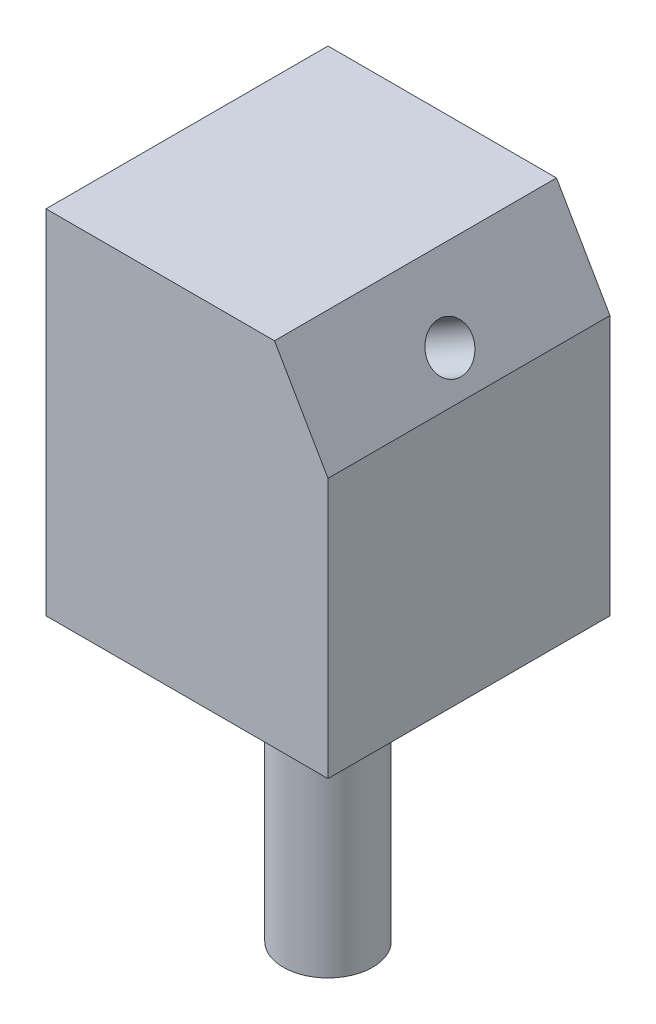
SolidWorks part; units mm, degrees
ref_plane "Alzado" through (0, 0, 0) normal (0, 0, 1) x (1, 0, 0)
ref_plane "Planta" through (0, 0, 0) normal (0, 1, 0) x (1, 0, 0)
ref_plane "Vista lateral" through (0, 0, 0) normal (1, 0, 0) x (0, 0, -1)
sketch "Croquis1" plane through (0, 0, 0) normal (0, 1, 0) x (1, 0, 0)
  line L1 (-6.1404, -5.7018) -> (13.8596, -5.7018)
  line L2 (-6.1404, -5.7018) -> (-6.1404, 14.2982)
  line L3 (-6.1404, 14.2982) -> (13.8596, 14.2982)
  line L4 (13.8596, -5.7018) -> (13.8596, 14.2982)
  dimension "D1" = 20
  dimension "D2" = 20
extrude "Saliente-Extruir1" add sketch "Croquis1" along normal blind 30
sketch "Croquis2" plane through (0, 0, 0) normal (0, 0, 1) x (1, 0, 0)
  line L0 (13.8596, 24.6924) -> (13.8596, 18.4443)
  line L1 (13.8596, 30) -> (13.8596, 0) construction
  line L2 (13.8596, 18.4443) -> (11.1508, 23.1246) construction
  line L3 (11.1508, 23.1246) -> (13.8596, 24.6924) construction
  line L5 (13.8596, 18.4443) -> (11.1508, 23.1246)
  line L6 (11.1508, 23.1246) -> (13.8596, 24.6924)
extrude "Cortar-Extruir1" cut sketch "Croquis2" against normal through all both and the other way through all
sketch "Croquis4" plane through (18.3783, 10.6373, 0) normal (0.8655, 0.5009, 0) x (0, 0, -1)
  circle A0 centre (4.2982, 11.7243) radius 1.5875
  dimension "D1" = 3.175
extrude "Cortar-Extruir2" cut sketch "Croquis4" against normal blind 30
sketch "Croquis7" plane through (0, 0, 0) normal (0, -1, 0) x (1, 0, 0)
  circle A0 centre (3.8596, -4.2982) radius 3.175
  dimension "D1" = 6.35
extrude "Saliente-Extruir2" add sketch "Croquis7" along normal blind 20
sketch "Croquis8" plane through (0, 0, 5.7018) normal (0, 0, 1) x (1, 0, 0)
  line L0 (12.5052, 20.7845) -> (-24.4883, -0.6272) construction
  line L1 (11.1508, 23.1246) -> (13.8596, 18.4443) construction
  line L2 (-6.1404, 0) -> (13.8596, 0) construction
  point P6 (3.8596, 0)
  dimension "D1" = 28.3479
sketch "Croquis9" plane through (0, 0, 5.7018) normal (0, 0, 1) x (1, 0, 0)
  line L12 (10.0653, 25) -> (-6.1404, 25)
  line L16 (13.8596, 18.4443) -> (10.0653, 25)
  line L17 (13.8596, 30) -> (13.8596, 18.4443)
  line L18 (13.8596, 30) -> (-6.1404, 30)
  line L21 (-6.1404, 30) -> (-6.1404, 25)
extrude "Cortar-Extruir3" cut sketch "Croquis9" against normal through all
